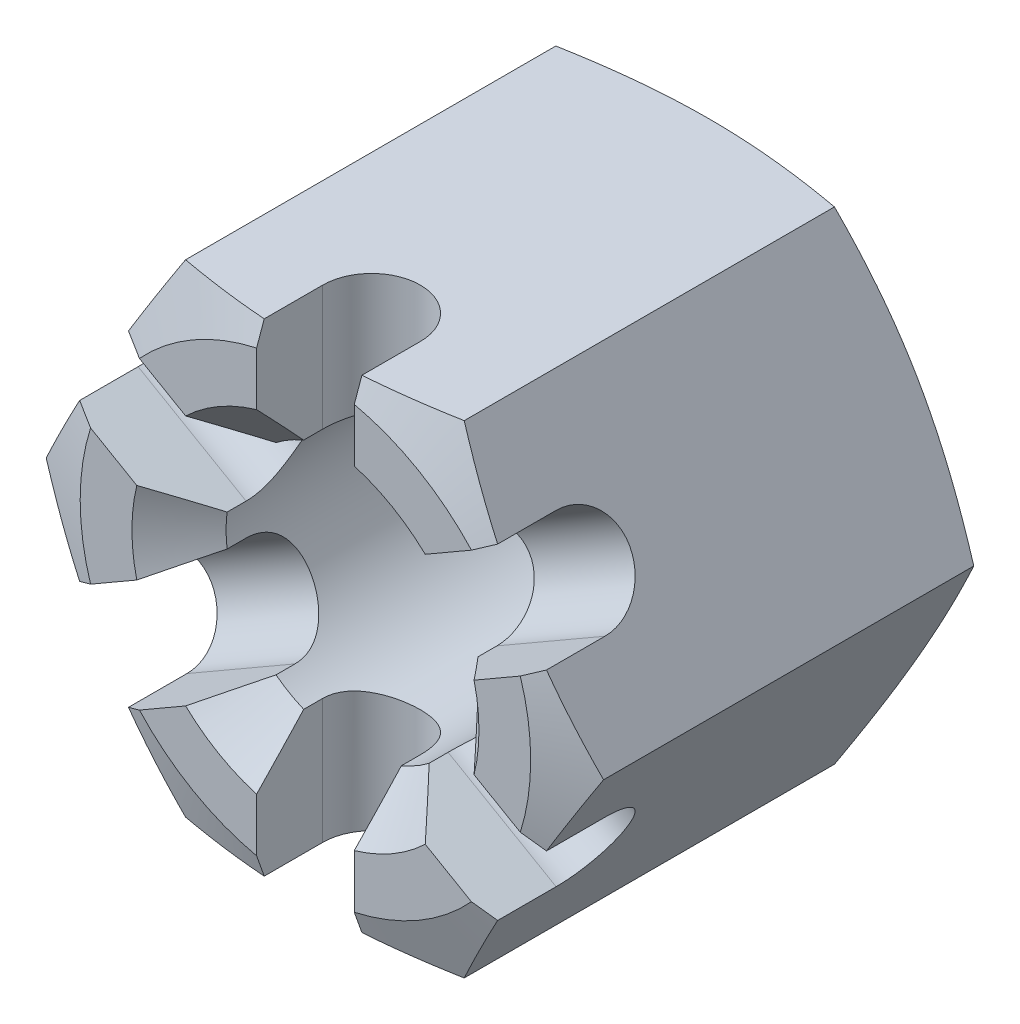
SolidWorks part; units mm, degrees
ref_plane "Front" through (0, 0, 0) normal (0, 0, 1) x (1, 0, 0)
ref_plane "Top" through (0, 0, 0) normal (0, 1, 0) x (1, 0, 0)
ref_plane "Right" through (0, 0, 0) normal (1, 0, 0) x (0, 0, -1)
other "Configuration Table"
sketch "Sketch1" plane through (0, 0, 0) normal (0, 0, 1) x (1, 0, 0)
  line L1 (6.0622, -10.5) -> (12.1244, 0)
  line L2 (12.1244, 0) -> (6.0622, 10.5)
  line L3 (6.0622, 10.5) -> (-6.0622, 10.5)
  line L4 (-6.0622, 10.5) -> (-12.1244, 0)
  line L5 (-12.1244, 0) -> (-6.0622, -10.5)
  line L6 (-6.0622, -10.5) -> (6.0622, -10.5)
  circle A0 centre (0, 0) radius 10.5 construction
  dimension "s" = 21
extrude "BaseNut" add sketch "Sketch1" against normal blind 17.8
sketch "Sketch2" plane through (-3.4718, 0, -17.3282) normal (0, 1, 0) x (0, 0, -1)
  line L0 (0.4718, 6.3282) -> (-0.3742, 8.6526)
  line L3 (-0.3742, 8.6526) -> (0.4718, 8.6526)
  line L4 (0.4718, 8.6526) -> (0.4718, 6.3282)
  line L5 (0, -3.4718) -> (-12.6262, -3.4718) construction
  line L6 (-17.3282, 6.3282) -> (-17.3282, 8.6526)
  line L8 (-17.3282, 8.6526) -> (-16.4822, 8.6526)
  line L9 (-16.4822, 8.6526) -> (-17.3282, 6.3282)
  dimension "dw" = 19.6
  dimension "D2" = 20
  dimension "D3" = 20
revolve "Double-Chamfer" cut sketch "Sketch2" angle 360 about L5
sketch "Sketch3" plane through (-4.2799, -1.7357, -17.8) normal (0, 0, -1) x (-1, 0, 0)
  line L0 (-4.2799, 1.7357) -> (-4.2799, 3.2357) construction
  circle A0 centre (-4.2799, 1.7357) radius 5.5
  circle A1 centre (-4.2799, 1.7357) radius 9.8 construction
  dimension "D1" = 11
  dimension "D2" = 1.5
extrude "Hole" cut sketch "Sketch3" against normal through all
cosmetic thread "ThreadCosmetic1" [suppressed] parameters "D2"=14
sketch "Sketch4" plane through (-15.7583, 0, -7.1083) normal (0, 1, 0) x (0, 0, -1)
  line L0 (10.6917, -23.3083) -> (8.6417, -21.2583)
  line L2 (8.6417, -21.2583) -> (10.6917, -21.2583)
  line L3 (10.6917, -21.2583) -> (10.6917, -23.3083)
  line L4 (0, -15.7583) -> (-22.8666, -15.7583) construction
  line L7 (-7.1083, -21.2583) -> (-5.0583, -21.2583)
  line L9 (-5.0583, -21.2583) -> (-7.1083, -23.3083)
  line L10 (-7.1083, -23.3083) -> (-7.1083, -21.2583)
  dimension "D1" = 15.1
  dimension "D2" = 45
  dimension "D3" = 45
revolve "EndChamfer" cut sketch "Sketch4" angle 360 about L4
sketch "Sketch5" plane through (-17.8, 0, -17.8) normal (0, 1, 0) x (0, 0, -1)
  line L0 (-17.8, -15.675) -> (-14.925, -15.675)
  line L2 (-14.925, -19.925) -> (-17.8, -19.925)
  line L3 (-17.8, -19.925) -> (-17.8, -15.675)
  line L6 (0, -25.35) -> (0, -10.25) construction
  line L8 (-17.8, -10.25) -> (-17.8, -25.35) construction
  arc A0 (-14.925, -15.675) -> (-14.925, -19.925) centre (-14.925, -17.8) cw
  point P2 (-12.8, -17.8)
  point P3 (0, -17.8)
  dimension "n" = 4.25
  dimension "W" = 12.8
extrude "Slot" cut sketch "Sketch5" against normal through all
pattern_circular "SlotPattern" count 6 over 360 about axis through (0, 0, 0) along (0, 0, 1) of "Slot"
sketch "Sketch6" plane through (-3.4767, 0, -17.3331) normal (0, 1, 0) x (0, 0, -1)
  line L0 (-17.3331, 0.5233) -> (-12.3331, 0.5233)
  line L1 (-12.3331, 0.5233) -> (-9.3761, 8.6477)
  line L2 (-9.3761, 8.6477) -> (-17.3331, 8.6477)
  line L3 (-17.3331, 8.6477) -> (-17.3331, 0.5233)
  line L7 (0, -3.4767) -> (-20.8098, -3.4767) construction
  line L8 (-17.3331, 6.3233) -> (-17.3331, 5.8709) construction
  line L9 (-0.3791, 8.6477) -> (-16.4871, 8.6477) construction
  dimension "D1" = 70
  dimension "D3" = 8
  dimension "D2" = 12.8
revolve "Cut-Revolve1" [suppressed] cut sketch "Sketch6" angle 360 about L7
sketch "Sketch7" plane through (0, 0, 0) normal (0, 1, 0) x (1, 0, 0)
  line L0 (4, 16.5) -> (5.5, 16.5)
  line L1 (5.5, 16.5) -> (6.799, 15.75)
  line L2 (6.799, 15.75) -> (5.5, 15)
  line L3 (5.5, 15) -> (4, 15)
  line L4 (4, 15) -> (4, 16.5)
  line L5 (0, 25.358) -> (0, -3.8405) construction
  line L6 (-5.5, 15.75) -> (5.5, 15.75) construction
  dimension "D1" = 1.5
  dimension "D2" = 11
revolve "Cut-Revolve10" [suppressed] cut sketch "Sketch7" angle 360 about L5
pattern_linear "LPattern10" [suppressed] count 8 spacing 1.8 along (0, 0, 1)
equation "\"D2@Sketch6\" = \"W@Sketch5\""
equation "\"D1@Sketch3\" = \"D2@ThreadCosmetic1\" - \"D2@Sketch3\" * 2"
equation "\"D2@Sketch7\" = \"D1@Sketch3\""
equation "\"D1@Sketch7\" = (  \"D2@ThreadCosmetic1\" - \"D1@Sketch3\" )  / 2"
equation "\"D3@LPattern10\" = \"D1@Sketch7\" * 1.2"
equation "\"D1@LPattern10\" = \"m@BaseNut\"  / \"D3@LPattern10\" - 2"
